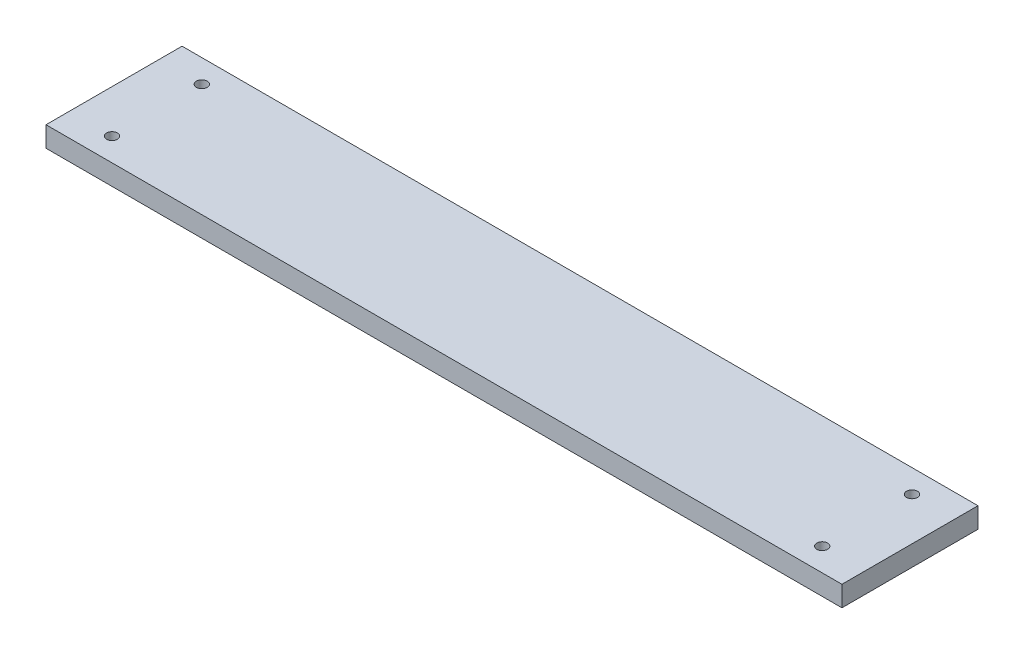
SolidWorks part; units mm, degrees
ref_plane "Alzado" through (0, 0, 0) normal (0, 0, 1) x (1, 0, 0)
ref_plane "Planta" through (0, 0, 0) normal (0, 1, 0) x (1, 0, 0)
ref_plane "Vista lateral" through (0, 0, 0) normal (1, 0, 0) x (0, 0, -1)
sketch "Croquis1" plane through (0, 0, 0) normal (0, 1, 0) x (1, 0, 0)
  line L0 (292.5, 100) -> (292.5, 0) construction
  line L1 (0, 0) -> (585, 0)
  line L2 (0, 0) -> (0, 100)
  line L3 (0, 100) -> (585, 100)
  line L4 (585, 0) -> (585, 100)
  line L5 (0, 50) -> (585, 50) construction
  circle A0 centre (31.5, 83) radius 4
  circle A1 centre (31.5, 17) radius 4
  circle A2 centre (553.5, 17) radius 4
  circle A3 centre (553.5, 83) radius 4
  dimension "D3" = 31.5
  dimension "D4" = 8
  dimension "D1" = 100
  dimension "D2" = 585
  dimension "D5" = 33
  dimension "D6" = 33
  dimension "D7" = 31.5
extrude "Saliente-Extruir1" add sketch "Croquis1" along normal blind 15
sketch "Croquis2" plane through (0, 0, 0) normal (0, -1, 0) x (1, 0, 0)
  line L0 (0, -100) -> (0, 0) construction
  line L1 (0, -50) -> (585, -50) construction
  line L2 (585, 0) -> (585, -100) construction
  line L3 (292.5, 0) -> (292.5, -100) construction
  line L4 (0, 0) -> (585, 0) construction
  line L5 (585, -100) -> (0, -100) construction
  circle A0 centre (30.5, -50) radius 11
  circle A1 centre (554.5, -50) radius 11
  dimension "D1" = 22
  dimension "D2" = 30.5
extrude "Cortar-Extruir1" cut sketch "Croquis2" against normal blind 7
